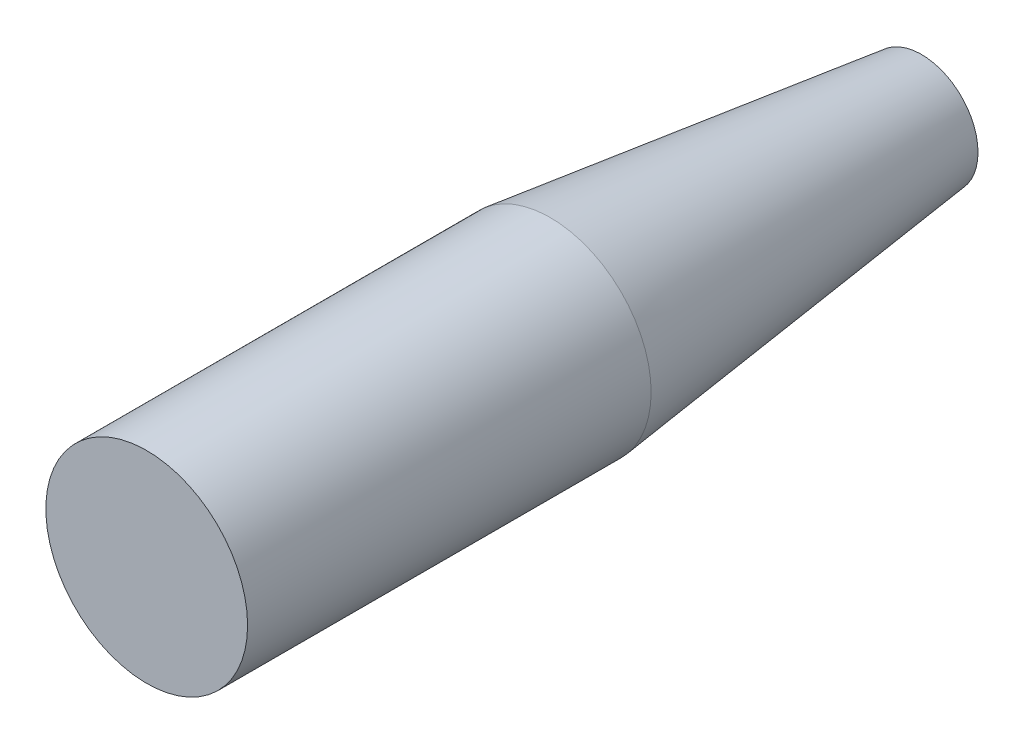
SolidWorks part; units mm, degrees
ref_plane "Front Plane" through (0, 0, 0) normal (0, 0, 1) x (1, 0, 0)
ref_plane "Top Plane" through (0, 0, 0) normal (0, 1, 0) x (1, 0, 0)
ref_plane "Right Plane" through (0, 0, 0) normal (1, 0, 0) x (0, 0, -1)
sketch "Sketch1" plane through (0, 0, 0) normal (0, 0, 1) x (1, 0, 0)
  circle A0 centre (0, 0) radius 6.25
  dimension "D1" = 12.5
extrude "Boss-Extrude1" add sketch "Sketch1" along normal blind 25
ref_axis "Axis1" through (0, 0, 25) along (0, 0, -1)
sketch "Sketch2" plane through (0, 0, 0) normal (0, 1, 0) x (1, 0, 0)
  line L0 (0, 0) -> (6.25, 0)
  line L1 (6.25, 0) -> (3.5, 23)
  line L2 (3.5, 23) -> (2.5, 23)
  line L4 (0, 21) -> (0, 0)
  line L8 (0, 21) -> (2.5, 21)
  line L9 (2.5, 23) -> (2.5, 21)
  dimension "D3" = 2.5
  dimension "D4" = 2
revolve "Revolve1" add sketch "Sketch2" angle 360 about axis through (0, 0, 25) along (0, 0, -1)
